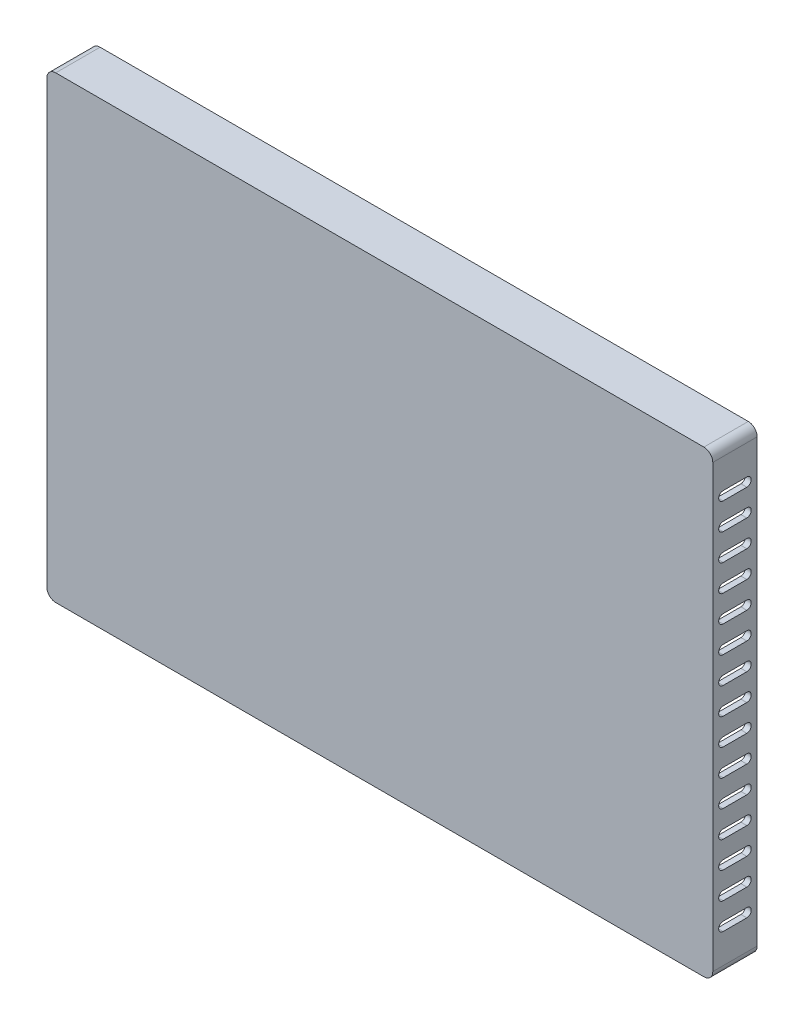
SolidWorks part; units mm, degrees
ref_plane "前视基准面" through (0, 0, 0) normal (0, 0, 1) x (1, 0, 0)
ref_plane "上视基准面" through (0, 0, 0) normal (0, 1, 0) x (1, 0, 0)
ref_plane "右视基准面" through (0, 0, 0) normal (1, 0, 0) x (0, 0, -1)
other "Configuration Table"
sketch "草图1" plane through (0, 0, 0) normal (0, 0, 1) x (1, 0, 0)
  line L1 (0, 0) -> (225, 0)
  line L2 (0, 0) -> (0, -155)
  line L3 (0, -155) -> (225, -155)
  line L4 (225, 0) -> (225, -155)
  dimension "D1" = 225
  dimension "D2" = 155
extrude "凸台-拉伸1" add sketch "草图1" along normal blind 15
fillet "圆角1" radius 3 4 edges at (225, 0, 7.5) (225, -155, 7.5) (0, 0, 7.5) (0, -155, 7.5)
shell "抽壳1" thickness 2
ref_plane "基准面1" through (112.5, 0, 0) normal (1, 0, 0) x (0, 0, -1)
sketch "草图4" plane through (0, 0, 0) normal (0, 0, -1) x (-1, 0, 0)
  line L16 (-223.8, -3) -> (-223.8, -152)
  line L17 (-222, -153.8) -> (-3, -153.8)
  line L18 (-1.2, -152) -> (-1.2, -3)
  line L19 (-3, -1.2) -> (-222, -1.2)
  line L20 (-223, -3) -> (-223, -152)
  line L21 (-222, -153) -> (-3, -153)
  line L22 (-2, -152) -> (-2, -3)
  line L23 (-3, -2) -> (-222, -2)
  line L24 (-223, -3) -> (-223, -152)
  line L25 (-222, -153) -> (-3, -153)
  line L26 (-2, -152) -> (-2, -3)
  line L27 (-3, -2) -> (-222, -2)
  arc A16 (-223.8, -152) -> (-222, -153.8) centre (-222, -152) ccw
  arc A17 (-3, -153.8) -> (-1.2, -152) centre (-3, -152) ccw
  arc A18 (-1.2, -3) -> (-3, -1.2) centre (-3, -3) ccw
  arc A19 (-222, -1.2) -> (-223.8, -3) centre (-222, -3) ccw
  arc A20 (-223, -152) -> (-222, -153) centre (-222, -152) ccw
  arc A21 (-3, -153) -> (-2, -152) centre (-3, -152) ccw
  arc A22 (-2, -3) -> (-3, -2) centre (-3, -3) ccw
  arc A23 (-222, -2) -> (-223, -3) centre (-222, -3) ccw
  arc A24 (-223, -152) -> (-222, -153) centre (-222, -152) ccw
  arc A25 (-3, -153) -> (-2, -152) centre (-3, -152) ccw
  arc A26 (-2, -3) -> (-3, -2) centre (-3, -3) ccw
  arc A27 (-222, -2) -> (-223, -3) centre (-222, -3) ccw
  dimension "D1" = 0
  dimension "D2" = 0.8
extrude "凸台-拉伸2" add sketch "草图4" along normal blind 0.5
sketch "草图5" plane through (0, 0, 0) normal (-1, 0, 0) x (0, 0, 1)
  line L0 (3.5, -14.5) -> (11.5, -14.5) construction
  line L1 (3.5, -13) -> (11.5, -13)
  line L2 (3.5, -16) -> (11.5, -16)
  line L3 (0, 0) -> (15, 0) construction
  line L4 (15, -3) -> (15, -152) construction
  line L5 (3.5, -23.5) -> (11.5, -23.5) construction
  line L6 (3.5, -22) -> (11.5, -22)
  line L7 (3.5, -25) -> (11.5, -25)
  line L8 (3.5, -32.5) -> (11.5, -32.5) construction
  line L9 (3.5, -31) -> (11.5, -31)
  line L10 (3.5, -34) -> (11.5, -34)
  line L11 (3.5, -41.5) -> (11.5, -41.5) construction
  line L12 (3.5, -40) -> (11.5, -40)
  line L13 (3.5, -43) -> (11.5, -43)
  line L14 (3.5, -50.5) -> (11.5, -50.5) construction
  line L15 (3.5, -49) -> (11.5, -49)
  line L16 (3.5, -52) -> (11.5, -52)
  line L17 (3.5, -59.5) -> (11.5, -59.5) construction
  line L18 (3.5, -58) -> (11.5, -58)
  line L19 (3.5, -61) -> (11.5, -61)
  line L20 (3.5, -68.5) -> (11.5, -68.5) construction
  line L21 (3.5, -67) -> (11.5, -67)
  line L22 (3.5, -70) -> (11.5, -70)
  line L23 (3.5, -77.5) -> (11.5, -77.5) construction
  line L24 (3.5, -76) -> (11.5, -76)
  line L25 (3.5, -79) -> (11.5, -79)
  line L26 (3.5, -86.5) -> (11.5, -86.5) construction
  line L27 (3.5, -85) -> (11.5, -85)
  line L28 (3.5, -88) -> (11.5, -88)
  line L29 (3.5, -95.5) -> (11.5, -95.5) construction
  line L30 (3.5, -94) -> (11.5, -94)
  line L31 (3.5, -97) -> (11.5, -97)
  line L32 (3.5, -104.5) -> (11.5, -104.5) construction
  line L33 (3.5, -103) -> (11.5, -103)
  line L34 (3.5, -106) -> (11.5, -106)
  line L35 (3.5, -113.5) -> (11.5, -113.5) construction
  line L36 (3.5, -112) -> (11.5, -112)
  line L37 (3.5, -115) -> (11.5, -115)
  line L38 (3.5, -122.5) -> (11.5, -122.5) construction
  line L39 (3.5, -121) -> (11.5, -121)
  line L40 (3.5, -124) -> (11.5, -124)
  line L41 (3.5, -131.5) -> (11.5, -131.5) construction
  line L42 (3.5, -130) -> (11.5, -130)
  line L43 (3.5, -133) -> (11.5, -133)
  line L44 (3.5, -140.5) -> (11.5, -140.5) construction
  line L45 (3.5, -139) -> (11.5, -139)
  line L46 (3.5, -142) -> (11.5, -142)
  arc A0 (3.5, -13) -> (3.5, -16) centre (3.5, -14.5) ccw
  arc A1 (11.5, -16) -> (11.5, -13) centre (11.5, -14.5) ccw
  arc A2 (3.5, -22) -> (3.5, -25) centre (3.5, -23.5) ccw
  arc A3 (11.5, -25) -> (11.5, -22) centre (11.5, -23.5) ccw
  arc A4 (3.5, -31) -> (3.5, -34) centre (3.5, -32.5) ccw
  arc A5 (11.5, -34) -> (11.5, -31) centre (11.5, -32.5) ccw
  arc A6 (3.5, -40) -> (3.5, -43) centre (3.5, -41.5) ccw
  arc A7 (11.5, -43) -> (11.5, -40) centre (11.5, -41.5) ccw
  arc A8 (3.5, -49) -> (3.5, -52) centre (3.5, -50.5) ccw
  arc A9 (11.5, -52) -> (11.5, -49) centre (11.5, -50.5) ccw
  arc A10 (3.5, -58) -> (3.5, -61) centre (3.5, -59.5) ccw
  arc A11 (11.5, -61) -> (11.5, -58) centre (11.5, -59.5) ccw
  arc A12 (3.5, -67) -> (3.5, -70) centre (3.5, -68.5) ccw
  arc A13 (11.5, -70) -> (11.5, -67) centre (11.5, -68.5) ccw
  arc A14 (3.5, -76) -> (3.5, -79) centre (3.5, -77.5) ccw
  arc A15 (11.5, -79) -> (11.5, -76) centre (11.5, -77.5) ccw
  arc A16 (3.5, -85) -> (3.5, -88) centre (3.5, -86.5) ccw
  arc A17 (11.5, -88) -> (11.5, -85) centre (11.5, -86.5) ccw
  arc A18 (3.5, -94) -> (3.5, -97) centre (3.5, -95.5) ccw
  arc A19 (11.5, -97) -> (11.5, -94) centre (11.5, -95.5) ccw
  arc A20 (3.5, -103) -> (3.5, -106) centre (3.5, -104.5) ccw
  arc A21 (11.5, -106) -> (11.5, -103) centre (11.5, -104.5) ccw
  arc A22 (3.5, -112) -> (3.5, -115) centre (3.5, -113.5) ccw
  arc A23 (11.5, -115) -> (11.5, -112) centre (11.5, -113.5) ccw
  arc A24 (3.5, -121) -> (3.5, -124) centre (3.5, -122.5) ccw
  arc A25 (11.5, -124) -> (11.5, -121) centre (11.5, -122.5) ccw
  arc A26 (3.5, -130) -> (3.5, -133) centre (3.5, -131.5) ccw
  arc A27 (11.5, -133) -> (11.5, -130) centre (11.5, -131.5) ccw
  arc A28 (3.5, -139) -> (3.5, -142) centre (3.5, -140.5) ccw
  arc A29 (11.5, -142) -> (11.5, -139) centre (11.5, -140.5) ccw
  point P2 (7.5, -14.5)
  point P14 (7.5, -23.5)
  point P21 (7.5, -32.5)
  point P28 (7.5, -41.5)
  point P35 (7.5, -50.5)
  point P42 (7.5, -59.5)
  point P49 (7.5, -68.5)
  point P56 (7.5, -77.5)
  point P63 (7.5, -86.5)
  point P70 (7.5, -95.5)
  point P77 (7.5, -104.5)
  point P84 (7.5, -113.5)
  point P91 (7.5, -122.5)
  point P98 (7.5, -131.5)
  point P105 (7.5, -140.5)
  dimension "D2" = 1.5
  dimension "D1" = 8
  dimension "D3" = 13
  dimension "D4" = 3.5
  dimension "D5" = 15
extrude "切除-拉伸1" cut sketch "草图5" against normal blind 3
mirror "镜向1" about plane through (112.5, 0, 0) normal (1, 0, 0) of "切除-拉伸1"
